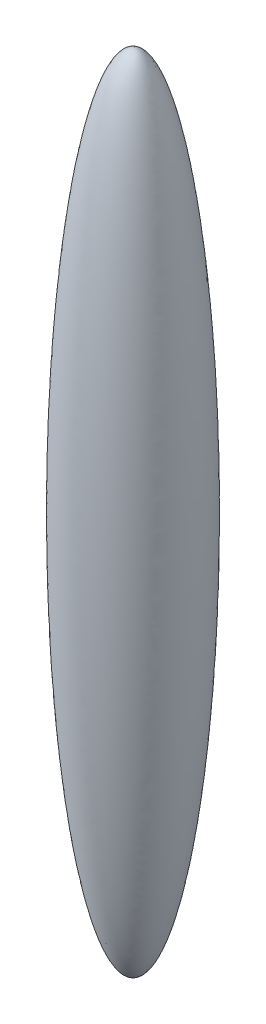
SolidWorks part; units mm, degrees
ref_plane "Front" through (0, 0, 0) normal (0, 0, 1) x (1, 0, 0)
ref_plane "Top" through (0, 0, 0) normal (0, 1, 0) x (1, 0, 0)
ref_plane "Right" through (0, 0, 0) normal (1, 0, 0) x (0, 0, -1)
sketch "Sketch1" plane through (0, 0, 0) normal (0, 0, 1) x (1, 0, 0)
  line L0 (0, 0) -> (0, 1000) construction
  line L1 (0, -50) -> (0, 50) construction
  line L2 (0, 1000) -> (0, 0)
  ellipse E0 centre (0, 500) end of major axis (0, 1000) minor radius 76.2 (0, 0) -> (0, 1000) ccw
  dimension "D1" = 1000
  dimension "D2" = 76.2
revolve "Revolve2" add sketch "Sketch1" angle 360 about L0
